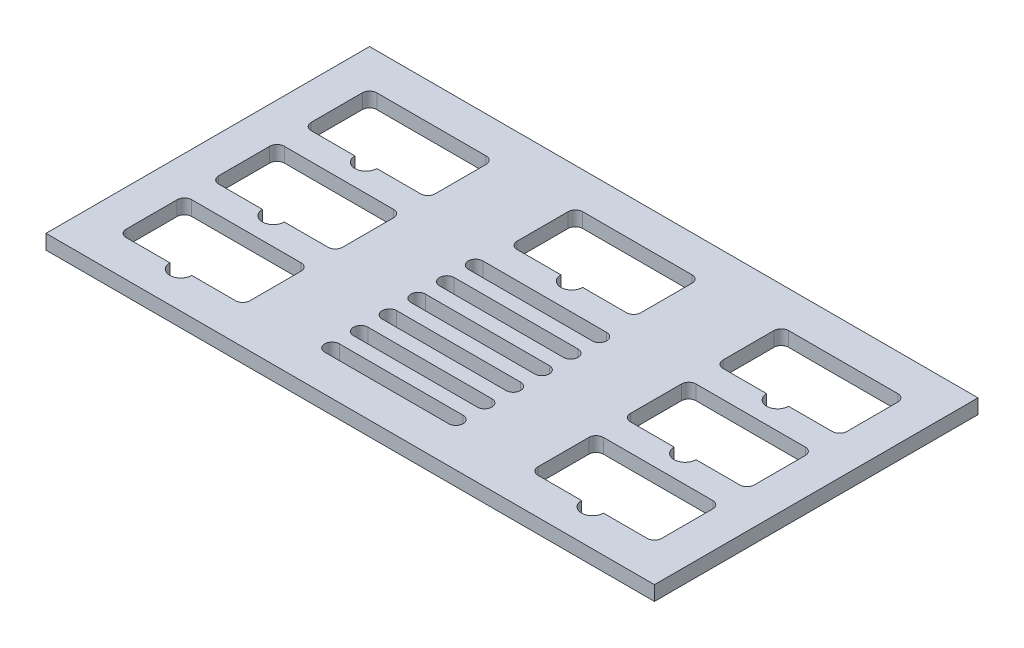
SolidWorks part; units mm, degrees
ref_plane "Front Plane" through (0, 0, 0) normal (0, 0, 1) x (1, 0, 0)
ref_plane "Top Plane" through (0, 0, 0) normal (0, 1, 0) x (1, 0, 0)
ref_plane "Right Plane" through (0, 0, 0) normal (1, 0, 0) x (0, 0, -1)
sketch "Sketch1" plane through (0, 0, 0) normal (0, 1, 0) x (1, 0, 0)
  line L0 (29.25, -9) -> (35.25, -9)
  line L1 (1, 0) -> (16, 0)
  line L2 (0, -1) -> (0, -8)
  line L3 (1, -9) -> (7, -9)
  line L4 (17, -1) -> (17, -8)
  line L5 (28.25, -1) -> (28.25, -8)
  line L6 (29.25, 0) -> (44.25, 0)
  line L7 (45.25, -1) -> (45.25, -8)
  line L8 (38.25, -9) -> (44.25, -9)
  line L9 (57.5, -9) -> (63.5, -9)
  line L10 (56.5, -1) -> (56.5, -8)
  line L11 (57.5, 0) -> (72.5, 0)
  line L12 (10, -9) -> (16, -9)
  line L13 (73.5, -1) -> (73.5, -8)
  line L14 (66.5, -9) -> (72.5, -9)
  line L15 (29.25, -21.7) -> (35.25, -21.7) [skipped]
  line L16 (28.25, -13.7) -> (28.25, -20.7) [skipped]
  line L17 (29.25, -12.7) -> (44.25, -12.7) [skipped]
  line L18 (45.25, -13.7) -> (45.25, -20.7) [skipped]
  line L19 (38.25, -21.7) -> (44.25, -21.7) [skipped]
  line L20 (57.5, -21.7) -> (63.5, -21.7)
  line L21 (56.5, -13.7) -> (56.5, -20.7)
  line L22 (57.5, -12.7) -> (72.5, -12.7)
  line L23 (73.5, -13.7) -> (73.5, -20.7)
  line L24 (66.5, -21.7) -> (72.5, -21.7)
  line L25 (29.25, -34.4) -> (35.25, -34.4) [skipped]
  line L26 (28.25, -26.4) -> (28.25, -33.4) [skipped]
  line L27 (29.25, -25.4) -> (44.25, -25.4) [skipped]
  line L28 (45.25, -26.4) -> (45.25, -33.4) [skipped]
  line L29 (38.25, -34.4) -> (44.25, -34.4) [skipped]
  line L30 (57.5, -34.4) -> (63.5, -34.4)
  line L31 (56.5, -26.4) -> (56.5, -33.4)
  line L32 (57.5, -25.4) -> (72.5, -25.4)
  line L33 (73.5, -26.4) -> (73.5, -33.4)
  line L34 (66.5, -34.4) -> (72.5, -34.4)
  line L35 (1, -21.7) -> (7, -21.7)
  line L36 (0, -13.7) -> (0, -20.7)
  line L37 (1, -12.7) -> (16, -12.7)
  line L38 (17, -13.7) -> (17, -20.7)
  line L39 (10, -21.7) -> (16, -21.7)
  line L40 (1, -34.4) -> (7, -34.4)
  line L41 (0, -26.4) -> (0, -33.4)
  line L42 (1, -25.4) -> (16, -25.4)
  line L43 (17, -26.4) -> (17, -33.4)
  line L44 (10, -34.4) -> (16, -34.4)
  line L45 (28.25, -16.64) -> (45.25, -16.64)
  line L46 (28.25, -12.7) -> (45.25, -12.7) construction
  line L47 (28.25, -18.64) -> (45.25, -18.64)
  line L48 (45.25, -34.4) -> (28.25, -34.4) construction
  line L49 (28.25, -16.64) -> (45.25, -16.64) construction
  line L50 (28.25, -12.7) -> (45.25, -12.7)
  line L51 (28.25, -20.58) -> (45.25, -20.58)
  line L52 (28.25, -14.7) -> (45.25, -14.7)
  line L53 (28.25, -22.58) -> (45.25, -22.58)
  line L54 (28.25, -20.58) -> (45.25, -20.58) construction
  line L55 (28.25, -24.52) -> (45.25, -24.52)
  line L56 (28.25, -26.52) -> (45.25, -26.52)
  line L57 (28.25, -24.52) -> (45.25, -24.52) construction
  line L58 (28.25, -28.46) -> (45.25, -28.46)
  line L59 (28.25, -30.46) -> (45.25, -30.46)
  line L60 (28.25, -28.46) -> (45.25, -28.46) construction
  line L61 (28.25, -32.4) -> (45.25, -32.4)
  line L62 (28.25, -34.4) -> (45.25, -34.4)
  line L63 (28.25, -32.4) -> (45.25, -32.4) construction
  line L65 (-5, 5) -> (78.5, 5)
  line L66 (-5, 5) -> (-5, -39.4)
  line L67 (-5, -39.4) -> (78.5, -39.4)
  line L68 (78.5, 5) -> (78.5, -39.4)
  arc A0 (16, 0) -> (17, -1) centre (16, -1) cw
  arc A1 (17, -8) -> (16, -9) centre (16, -8) cw
  arc A2 (1, -9) -> (0, -8) centre (1, -8) cw
  arc A3 (0, -1) -> (1, 0) centre (1, -1) cw
  arc A4 (29.25, -9) -> (28.25, -8) centre (29.25, -8) cw
  arc A5 (28.25, -1) -> (29.25, 0) centre (29.25, -1) cw
  arc A6 (44.25, 0) -> (45.25, -1) centre (44.25, -1) cw
  arc A7 (45.25, -8) -> (44.25, -9) centre (44.25, -8) cw
  arc A8 (35.25, -9) -> (38.25, -9) centre (36.75, -9) ccw
  arc A9 (57.5, -9) -> (56.5, -8) centre (57.5, -8) cw
  arc A10 (56.5, -1) -> (57.5, 0) centre (57.5, -1) cw
  arc A11 (72.5, 0) -> (73.5, -1) centre (72.5, -1) cw
  arc A12 (7, -9) -> (10, -9) centre (8.5, -9) ccw
  arc A13 (73.5, -8) -> (72.5, -9) centre (72.5, -8) cw
  arc A14 (63.5, -9) -> (66.5, -9) centre (65, -9) ccw
  arc A15 (29.25, -21.7) -> (28.25, -20.7) centre (29.25, -20.7) cw [skipped]
  arc A16 (28.25, -13.7) -> (29.25, -12.7) centre (29.25, -13.7) cw [skipped]
  arc A17 (44.25, -12.7) -> (45.25, -13.7) centre (44.25, -13.7) cw [skipped]
  arc A18 (45.25, -20.7) -> (44.25, -21.7) centre (44.25, -20.7) cw [skipped]
  arc A19 (35.25, -21.7) -> (38.25, -21.7) centre (36.75, -21.7) ccw [skipped]
  arc A20 (57.5, -21.7) -> (56.5, -20.7) centre (57.5, -20.7) cw
  arc A21 (56.5, -13.7) -> (57.5, -12.7) centre (57.5, -13.7) cw
  arc A22 (72.5, -12.7) -> (73.5, -13.7) centre (72.5, -13.7) cw
  arc A23 (73.5, -20.7) -> (72.5, -21.7) centre (72.5, -20.7) cw
  arc A24 (63.5, -21.7) -> (66.5, -21.7) centre (65, -21.7) ccw
  arc A25 (29.25, -34.4) -> (28.25, -33.4) centre (29.25, -33.4) cw [skipped]
  arc A26 (28.25, -26.4) -> (29.25, -25.4) centre (29.25, -26.4) cw [skipped]
  arc A27 (44.25, -25.4) -> (45.25, -26.4) centre (44.25, -26.4) cw [skipped]
  arc A28 (45.25, -33.4) -> (44.25, -34.4) centre (44.25, -33.4) cw [skipped]
  arc A29 (35.25, -34.4) -> (38.25, -34.4) centre (36.75, -34.4) ccw [skipped]
  arc A30 (57.5, -34.4) -> (56.5, -33.4) centre (57.5, -33.4) cw
  arc A31 (56.5, -26.4) -> (57.5, -25.4) centre (57.5, -26.4) cw
  arc A32 (72.5, -25.4) -> (73.5, -26.4) centre (72.5, -26.4) cw
  arc A33 (73.5, -33.4) -> (72.5, -34.4) centre (72.5, -33.4) cw
  arc A34 (63.5, -34.4) -> (66.5, -34.4) centre (65, -34.4) ccw
  arc A35 (1, -21.7) -> (0, -20.7) centre (1, -20.7) cw
  arc A36 (0, -13.7) -> (1, -12.7) centre (1, -13.7) cw
  arc A37 (16, -12.7) -> (17, -13.7) centre (16, -13.7) cw
  arc A38 (17, -20.7) -> (16, -21.7) centre (16, -20.7) cw
  arc A39 (7, -21.7) -> (10, -21.7) centre (8.5, -21.7) ccw
  arc A40 (1, -34.4) -> (0, -33.4) centre (1, -33.4) cw
  arc A41 (0, -26.4) -> (1, -25.4) centre (1, -26.4) cw
  arc A42 (16, -25.4) -> (17, -26.4) centre (16, -26.4) cw
  arc A43 (17, -33.4) -> (16, -34.4) centre (16, -33.4) cw
  arc A44 (7, -34.4) -> (10, -34.4) centre (8.5, -34.4) ccw
  arc A45 (28.25, -12.7) -> (28.25, -14.7) centre (28.25, -13.7) ccw
  arc A46 (45.25, -14.7) -> (45.25, -12.7) centre (45.25, -13.7) ccw
  arc A47 (28.25, -16.64) -> (28.25, -18.64) centre (28.25, -17.64) ccw
  arc A48 (45.25, -18.64) -> (45.25, -16.64) centre (45.25, -17.64) ccw
  arc A49 (28.25, -20.58) -> (28.25, -22.58) centre (28.25, -21.58) ccw
  arc A50 (45.25, -22.58) -> (45.25, -20.58) centre (45.25, -21.58) ccw
  arc A51 (28.25, -24.52) -> (28.25, -26.52) centre (28.25, -25.52) ccw
  arc A52 (45.25, -26.52) -> (45.25, -24.52) centre (45.25, -25.52) ccw
  arc A53 (28.25, -28.46) -> (28.25, -30.46) centre (28.25, -29.46) ccw
  arc A54 (45.25, -30.46) -> (45.25, -28.46) centre (45.25, -29.46) ccw
  arc A55 (28.25, -32.4) -> (28.25, -34.4) centre (28.25, -33.4) ccw
  arc A56 (45.25, -34.4) -> (45.25, -32.4) centre (45.25, -33.4) ccw
  point P13 (0, 0)
  dimension "D1" = 1
  dimension "D4" = 6
  dimension "D5" = 5
  dimension "D6" = 5
  dimension "D2" = 3
  dimension "D3" = 3
extrude "Boss-Extrude1" add sketch "Sketch1" along normal blind 2
